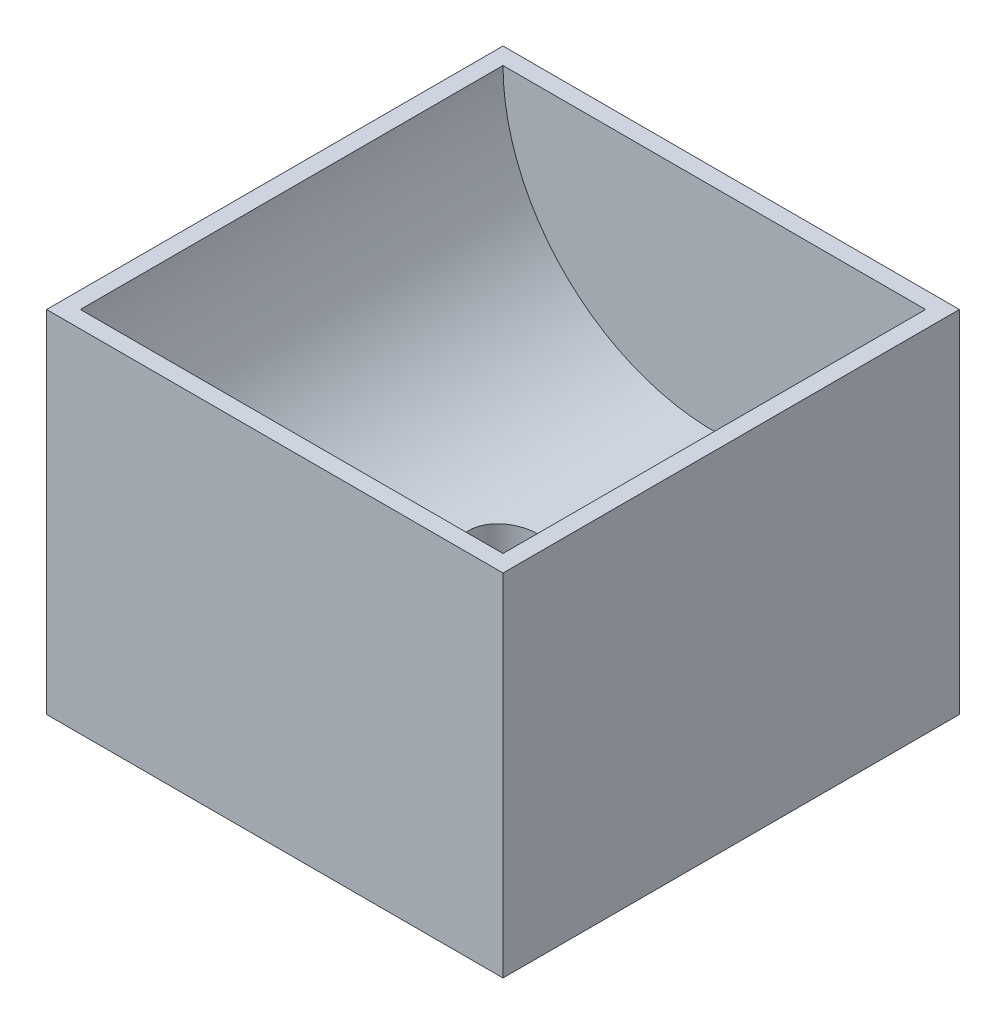
SolidWorks part; units mm, degrees
ref_plane "Front Plane" through (0, 0, 0) normal (0, 0, 1) x (1, 0, 0)
ref_plane "Top Plane" through (0, 0, 0) normal (0, 1, 0) x (1, 0, 0)
ref_plane "Right Plane" through (0, 0, 0) normal (1, 0, 0) x (0, 0, -1)
sketch "Sketch1" plane through (0, 0, 0) normal (0, 0, 1) x (1, 0, 0)
  line L0 (25, 0) -> (27, 0)
  line L1 (-27, 0) -> (-25, 0)
  line L2 (-27, 0) -> (-27, -28)
  line L3 (-27, -28) -> (27, -28)
  line L4 (27, 0) -> (27, -28)
  arc A0 (-25, 0) -> (25, 0) centre (0, 0) ccw
  dimension "D1" = 50
  dimension "D2" = 2
  dimension "D3" = 2
  dimension "D4" = 3
extrude "Boss-Extrude1" add sketch "Sketch1" along normal mid plane 50
sketch "Sketch2" plane through (0, 0, 25) normal (0, 0, 1) x (1, 0, 0)
  line L1 (-27, 0) -> (27, 0)
  line L2 (-27, 0) -> (-27, -28)
  line L3 (-27, -28) -> (27, -28)
  line L4 (27, 0) -> (27, -28)
extrude "Boss-Extrude2" add sketch "Sketch2" along normal blind 2
sketch "Sketch3" plane through (0, 0, -25) normal (0, 0, -1) x (-1, 0, 0)
  line L1 (-27, 0) -> (27, 0)
  line L2 (-27, 0) -> (-27, -28)
  line L3 (-27, -28) -> (27, -28)
  line L4 (27, 0) -> (27, -28)
extrude "Boss-Extrude3" add sketch "Sketch3" along normal blind 2
sketch "Sketch4" plane through (0, -28, 0) normal (0, -1, 0) x (1, 0, 0)
  circle A0 centre (0, 0) radius 4.05
  dimension "D1" = 8.1
extrude "Cut-Extrude2" cut sketch "Sketch4" against normal through all
sketch "Sketch5" plane through (0, -28, 0) normal (0, -1, 0) x (1, 0, 0)
  line L1 (-7.5056, 0) -> (-3.7528, -6.5)
  line L2 (-3.7528, -6.5) -> (3.7528, -6.5)
  line L3 (3.7528, -6.5) -> (7.5056, 0)
  line L4 (7.5056, 0) -> (3.7528, 6.5)
  line L5 (3.7528, 6.5) -> (-3.7528, 6.5)
  line L6 (-3.7528, 6.5) -> (-7.5056, 0)
  line L7 (-27, -27) -> (27, -27)
  line L8 (-27, -27) -> (-27, 27)
  line L9 (-27, 27) -> (27, 27)
  line L10 (27, -27) -> (27, 27)
  circle A0 centre (0, 0) radius 6.5 construction
  dimension "D1" = 13
extrude "Boss-Extrude4" add sketch "Sketch5" along normal blind 13.5
sketch "Sketch6" plane through (0, -41.5, 0) normal (0, -1, 0) x (1, 0, 0)
  circle A0 centre (0, 0) radius 8
  dimension "D1" = 16
extrude "Cut-Extrude3" cut sketch "Sketch6" against normal blind 7
